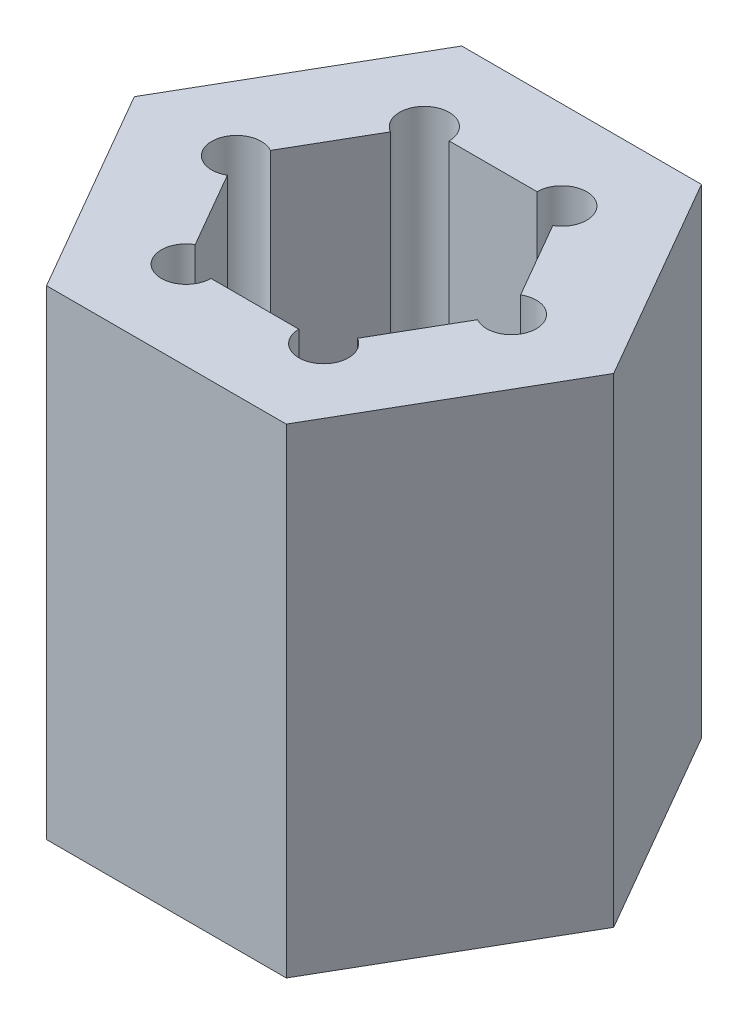
SolidWorks part; units mm, degrees
ref_plane "Front Plane" through (0, 0, 0) normal (0, 0, 1) x (1, 0, 0)
ref_plane "Top Plane" through (0, 0, 0) normal (0, 1, 0) x (1, 0, 0)
ref_plane "Right Plane" through (0, 0, 0) normal (1, 0, 0) x (0, 0, -1)
sketch "Sketch1" plane through (0, 0, 0) normal (0, 1, 0) x (1, 0, 0)
  line L1 (4.1569, 0) -> (2.0785, 3.6)
  line L2 (2.0785, 3.6) -> (-2.0785, 3.6)
  line L3 (-2.0785, 3.6) -> (-4.1569, 0)
  line L4 (-4.1569, 0) -> (-2.0785, -3.6)
  line L5 (-2.0785, -3.6) -> (2.0785, -3.6)
  line L6 (2.0785, -3.6) -> (4.1569, 0)
  line L7 (-3.6229, 6.275) -> (-7.2457, 0)
  line L8 (-7.2457, 0) -> (-3.6229, -6.275)
  line L9 (-3.6229, -6.275) -> (3.6229, -6.275)
  line L10 (3.6229, -6.275) -> (7.2457, 0)
  line L11 (7.2457, 0) -> (3.6229, 6.275)
  line L12 (3.6229, 6.275) -> (-3.6229, 6.275)
  circle A0 centre (0, 0) radius 3.6 construction
  circle A1 centre (0, 0) radius 6.275 construction
  dimension "D1" = 7.2
  dimension "D2" = 12.55
extrude "Boss-Extrude1" add sketch "Sketch1" along normal blind 14.5
sketch "Sketch2" plane through (0, 14.5, 0) normal (0, 1, 0) x (1, 0, 0)
  line L0 (2.0785, 3.6) -> (-2.0785, 3.6) construction
  circle A0 centre (-2.0785, 3.6) radius 0.75
  circle A1 centre (2.0785, 3.6) radius 0.75
  circle A2 centre (4.1569, 0) radius 0.75
  circle A3 centre (2.0785, -3.6) radius 0.75
  circle A4 centre (-2.0785, -3.6) radius 0.75
  circle A5 centre (-4.1569, 0) radius 0.75
  point P4 (2.0785, 3.6)
  point P18 (0, 0)
  dimension "D2" = 1.5
  dimension "D1" = 6
extrude "Cut-Extrude1" cut sketch "Sketch2" against normal through all
